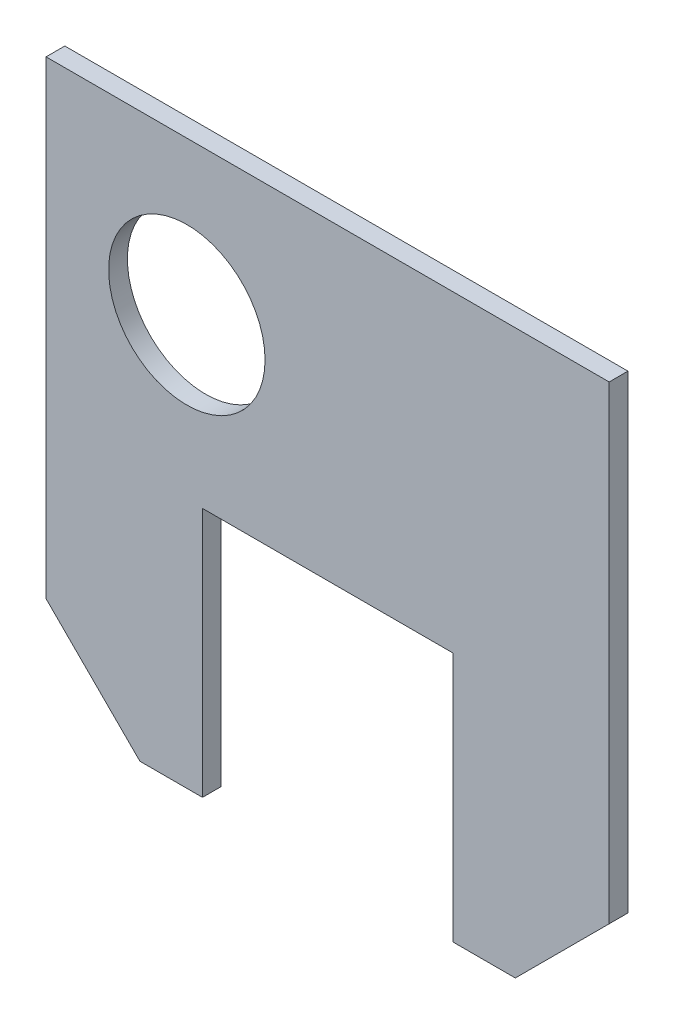
SolidWorks part; units mm, degrees
material "3.3535 (EN-AW 5754)"
ref_plane "Plan de face" through (0, 0, 0) normal (0, 0, 1) x (1, 0, 0)
ref_plane "Plan de dessus" through (0, 0, 0) normal (0, 1, 0) x (1, 0, 0)
ref_plane "Plan de droite" through (0, 0, 0) normal (1, 0, 0) x (0, 0, -1)
sketch "Esquisse1" plane through (0, 0, 0) normal (0, 0, 1) x (1, 0, 0)
  line L0 (3.7204, -58.2202) -> (-11.2796, -43.2202)
  line L1 (-11.2796, 31.7798) -> (33.7204, 31.7798)
  line L2 (-11.2796, 31.7798) -> (-11.2796, -43.2202)
  line L3 (3.7204, -58.2202) -> (13.7204, -58.2202)
  line L4 (33.7204, 31.7798) -> (33.7204, -18.2202)
  line L6 (13.7204, -58.2202) -> (13.7204, -18.2202)
  line L7 (13.7204, -18.2202) -> (33.7204, -18.2202)
  dimension "D1" = 45
  dimension "D2" = 20
  dimension "D3" = 40
  dimension "D4" = 45
  dimension "D5" = 15
  dimension "D6" = 90
extrude "Extrusion1" add sketch "Esquisse1" along normal blind 3
mirror "Symétrie1" about plane through (33.7204, 31.7798, 3) normal (-1, 0, 0) of "Extrusion1"
sketch "Esquisse2" plane through (0, 0, 3) normal (0, 0, 1) x (1, 0, 0)
  line L0 (13.7204, -58.2202) -> (13.7204, -18.2202) construction
  line L1 (13.7204, -18.2202) -> (53.7204, -18.2202) construction
  line L3 (-11.2796, 31.7798) -> (-11.2796, -43.2202) construction
  circle A0 centre (11.2204, 7.3252) radius 12.5
  point P2 (33.7204, -38.2202)
  point P5 (33.7204, -18.2202)
  dimension "D4" = 25
  dimension "D1" = 20
  dimension "D2" = 20
  dimension "D3" = 50.8
  dimension "D6" = 22.5
extrude "Enlèv. mat.-Extru.1" cut sketch "Esquisse2" against normal through all
